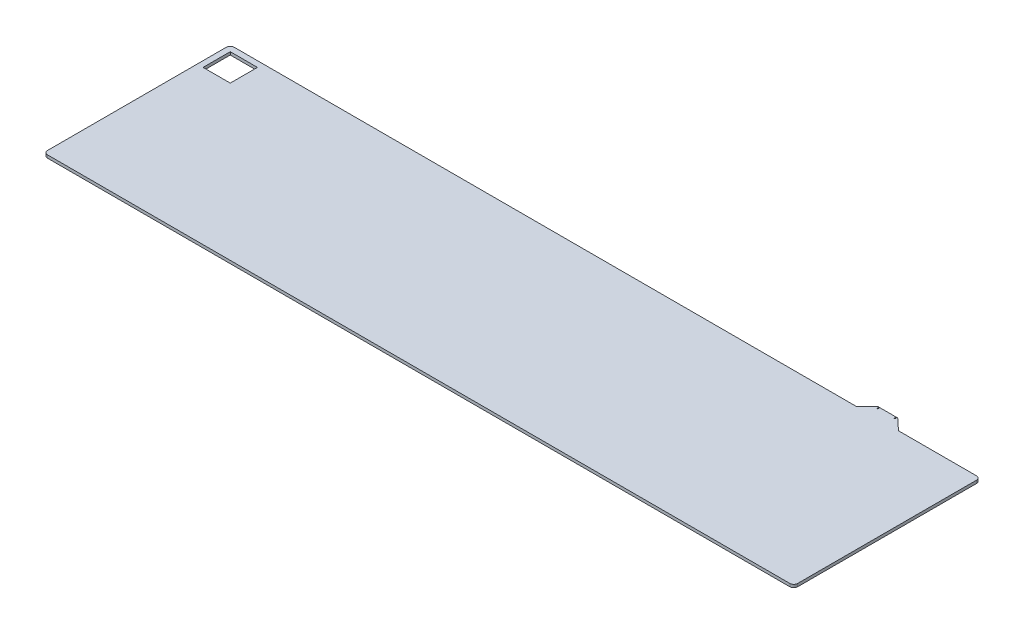
SolidWorks part; units mm, degrees
ref_plane "Front" through (0, 0, 0) normal (0, 0, 1) x (1, 0, 0)
ref_plane "Top" through (0, 0, 0) normal (0, 1, 0) x (1, 0, 0)
ref_plane "Right" through (0, 0, 0) normal (1, 0, 0) x (0, 0, -1)
sketch "Sketch1" plane through (0, 0, 0) normal (0, 1, 0) x (1, 0, 0)
  line L1 (2, 0) -> (384, 0)
  line L2 (0, 2) -> (0, 94)
  line L3 (2, 96) -> (384, 96)
  line L4 (386, 2) -> (386, 94)
  arc A0 (384, 0) -> (386, 2) centre (384, 2) ccw
  arc A1 (384, 96) -> (386, 94) centre (384, 94) cw
  arc A2 (2, 0) -> (0, 2) centre (2, 2) cw
  arc A3 (0, 94) -> (2, 96) centre (2, 94) cw
  point P11 (0, 0)
  dimension "D3" = 2
  dimension "D1" = 386
  dimension "D2" = 96
extrude "Boss-Extrude1" add sketch "Sketch1" along normal blind 1.5
sketch "Sketch2" plane through (0, 1.5, 0) normal (0, 1, 0) x (1, 0, 0)
  line L0 (343.8928, 96) -> (338, 101.5)
  line L1 (384, 96) -> (2, 96) construction
  line L2 (338, 101.5) -> (328, 101.5)
  line L3 (328, 101.5) -> (322.1072, 96)
  line L4 (322.1072, 96) -> (343.8928, 96)
  line L5 (386, 2) -> (386, 94) construction
  dimension "D1" = 5.8928
  dimension "D2" = 5.5
  dimension "D3" = 10
  dimension "D4" = 48
extrude "Boss-Extrude2" add sketch "Sketch2" against normal blind 1.5
sketch "Sketch3" plane through (0, 1.5, 0) normal (0, 1, 0) x (1, 0, 0)
  line L0 (338, 101.5) -> (328, 101.5) construction
  line L14 (328.15, 101.5) -> (337.85, 101.5) construction
  line L15 (328.15, 101.5) -> (328.15, 90.2) construction
  line L16 (328.15, 90.2) -> (337.85, 90.2) construction
  line L17 (337.85, 101.5) -> (337.85, 90.2) construction
  line L18 (337.8433, 103.5) -> (332.3757, 103.5) construction
  line L19 (328.32, 101.25) -> (328.82, 101.25)
  line L20 (328.32, 101.25) -> (328.32, 100.45)
  line L21 (328.32, 100.45) -> (328.82, 100.45)
  line L22 (328.82, 101.25) -> (328.82, 100.45)
  line L23 (337.68, 101.25) -> (337.18, 101.25)
  line L24 (337.68, 101.25) -> (337.68, 100.45)
  line L25 (337.68, 100.45) -> (337.18, 100.45)
  line L26 (337.18, 101.25) -> (337.18, 100.45)
  point P14 (328.57, 100.45)
  point P19 (333, 101.5)
  point P20 (337.68, 100.85)
  dimension "D1" = 9.7
  dimension "D2" = 11.3
  dimension "D3" = 0.8
  dimension "D4" = 8.36
  dimension "D5" = 0.15
  dimension "D6" = 2.25
  dimension "D7" = 4.18
  dimension "D8" = 0.5
  dimension "D9" = 0.5
  dimension "D10" = 2
extrude "Cut-Extrude1" cut sketch "Sketch3" against normal through all
sketch "Sketch4" plane through (0, 0, 0) normal (0, -1, 0) x (1, 0, 0)
  line L1 (375.5351, -6.4084) -> (10.2449, -6.4084)
  line L2 (375.5351, -6.4084) -> (375.5351, -86.0349)
  line L3 (375.5351, -86.0349) -> (10.2449, -86.0349)
  line L4 (10.2449, -6.4084) -> (10.2449, -86.0349)
extrude "Boss-Extrude3" add sketch "Sketch4" along normal blind 1.6
sketch "Sketch5" plane through (0, 1.5, 0) normal (0, 1, 0) x (1, 0, 0)
  line L1 (3, 93) -> (17, 93)
  line L2 (3, 93) -> (3, 79)
  line L3 (3, 79) -> (17, 79)
  line L4 (17, 93) -> (17, 79)
  line L6 (322.1072, 96) -> (2, 96) construction
  line L7 (0, 94) -> (0, 2) construction
  point P6 (3, 86)
  point P9 (10, 93)
  dimension "D1" = 14
  dimension "D2" = 14
  dimension "D3" = 10
  dimension "D4" = 10
extrude "Cut-Extrude2" cut sketch "Sketch5" against normal through all
